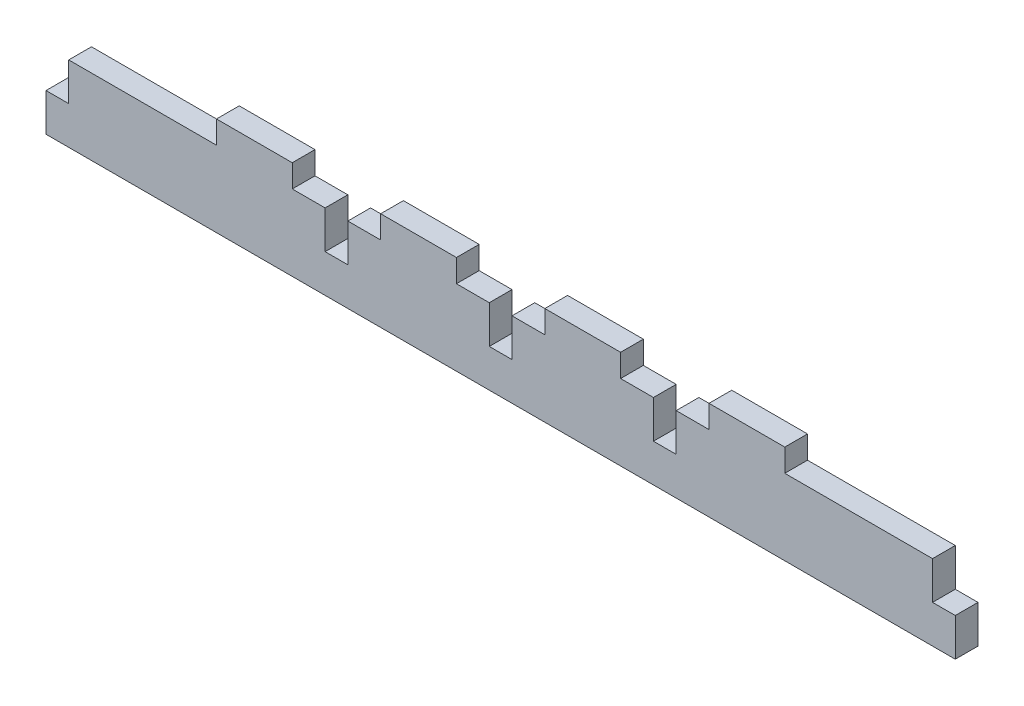
SolidWorks part; units mm, degrees
ref_plane "Front Plane" through (0, 0, 0) normal (0, 0, 1) x (1, 0, 0)
ref_plane "Top Plane" through (0, 0, 0) normal (0, 1, 0) x (1, 0, 0)
ref_plane "Right Plane" through (0, 0, 0) normal (1, 0, 0) x (0, 0, -1)
sketch "Model" plane through (0, 0, 0) normal (0, 0, 1) x (1, 0, 0)
  line L0 (112.5, 30) -> (171, 30)
  line L1 (-180, 0) -> (180, 0)
  line L2 (-180, 0) -> (-180, 15)
  line L3 (-171, 30) -> (-112.5, 30)
  line L4 (180, 0) -> (180, 15)
  line L5 (-180, 15) -> (-171, 15)
  line L8 (-171, 15) -> (-171, 30)
  line L9 (180, 15) -> (171, 15)
  line L10 (69.5, 30) -> (82.5, 30)
  line L11 (47.5, 30) -> (60.5, 30)
  line L12 (171, 15) -> (171, 30)
  line L13 (4.5, 30) -> (17.5, 30)
  line L14 (112.5, 30) -> (112.5, 39)
  line L15 (112.5, 39) -> (82.5, 39)
  line L16 (82.5, 30) -> (82.5, 39)
  line L18 (-112.5, 30) -> (-112.5, 39)
  line L19 (-112.5, 39) -> (-82.5, 39)
  line L20 (-82.5, 30) -> (-82.5, 39)
  line L21 (-82.5, 30) -> (-69.5, 30)
  line L22 (-69.5, 30) -> (-69.5, 15)
  line L23 (-69.5, 15) -> (-60.5, 15)
  line L24 (-60.5, 30) -> (-60.5, 15)
  line L25 (-60.5, 30) -> (-47.5, 30)
  line L26 (-47.5, 30) -> (-47.5, 39)
  line L27 (-47.5, 39) -> (-17.5, 39)
  line L28 (-17.5, 30) -> (-17.5, 39)
  line L29 (-17.5, 30) -> (-4.5, 30)
  line L30 (69.5, 30) -> (69.5, 15)
  line L31 (69.5, 15) -> (60.5, 15)
  line L32 (60.5, 30) -> (60.5, 15)
  line L34 (47.5, 30) -> (47.5, 39)
  line L35 (47.5, 39) -> (17.5, 39)
  line L36 (17.5, 30) -> (17.5, 39)
  line L38 (4.5, 30) -> (4.5, 15)
  line L39 (4.5, 15) -> (-4.5, 15)
  line L40 (-4.5, 30) -> (-4.5, 15)
  dimension "D2" = 9
  dimension "D4" = 9
  dimension "D6" = 15
  dimension "D8" = 360
  dimension "D10" = 30
  dimension "D14" = 30
  dimension "D3" = 35
extrude "Boss-Extrude1" add sketch "Model" along normal blind 9
equation "\"tab-width-large\" = 30mm ' Width of the large version of the Tab"
equation "\"baseplate-height\" = 360mm"
equation "\"material-thickness\" = 9mm"
equation "\"D2@Model\"= \"material-thickness\""
equation "\"D4@Model\" = \"material-thickness\""
equation "\"D1@Boss-Extrude1\" = \"material-thickness\""
equation "\"D8@Model\"=\"baseplate-height\""
equation "\"D14@Model\"=\"tab-width-large\""
